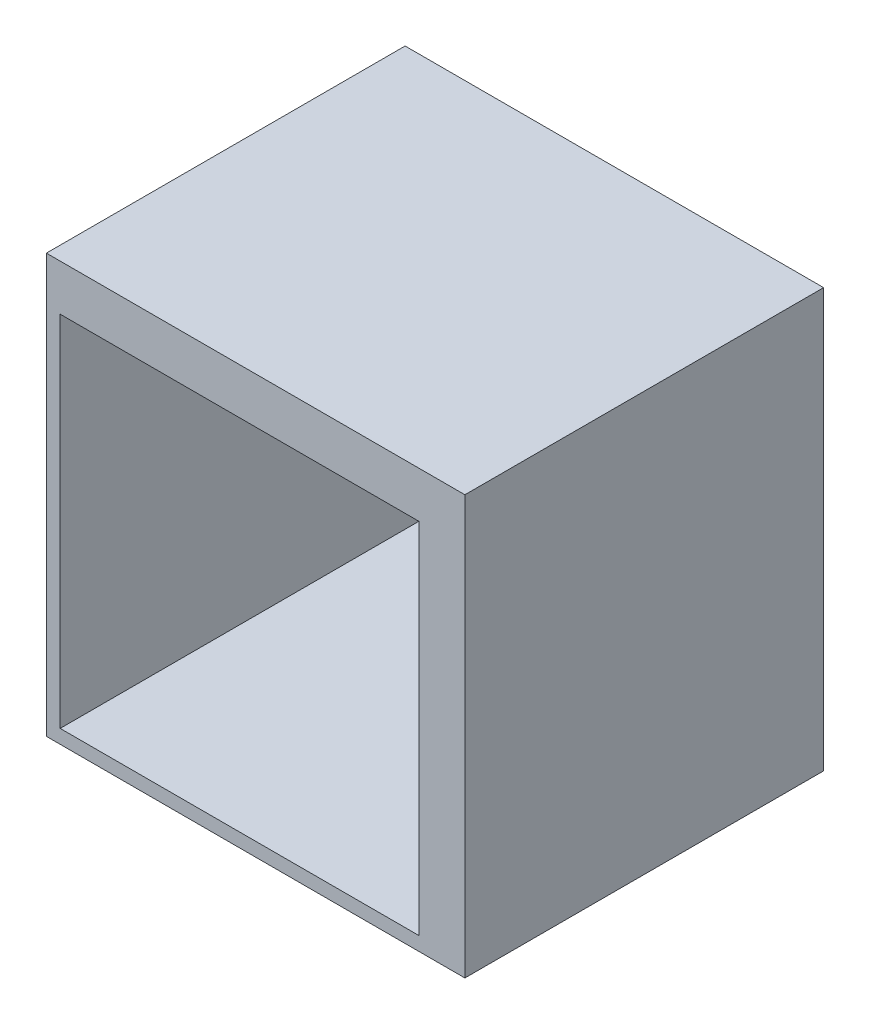
SolidWorks part; units mm, degrees
ref_plane "Plan de face" through (0, 0, 0) normal (0, 0, 1) x (1, 0, 0)
ref_plane "Plan de dessus" through (0, 0, 0) normal (0, 1, 0) x (1, 0, 0)
ref_plane "Plan de droite" through (0, 0, 0) normal (1, 0, 0) x (0, 0, -1)
sketch "Esquisse1" plane through (0, 0, 0) normal (0, 0, 1) x (1, 0, 0)
  line L1 (-94.3709, 348.2476) -> (295.6291, 348.2476)
  line L2 (-94.3709, 348.2476) -> (-94.3709, -41.7524)
  line L3 (-94.3709, -41.7524) -> (295.6291, -41.7524)
  line L4 (295.6291, 348.2476) -> (295.6291, -41.7524)
  line L5 (-109.3709, 398.2476) -> (345.6291, 398.2476)
  line L6 (-109.3709, 398.2476) -> (-109.3709, -56.7524)
  line L7 (-109.3709, -56.7524) -> (345.6291, -56.7524)
  line L8 (345.6291, 398.2476) -> (345.6291, -56.7524)
  dimension "D1" = 390
  dimension "D2" = 390
  dimension "D3" = 50
  dimension "D4" = 50
  dimension "D5" = 15
  dimension "D6" = 15
extrude "Boss.-Extru.1" add sketch "Esquisse1" along normal blind 390
